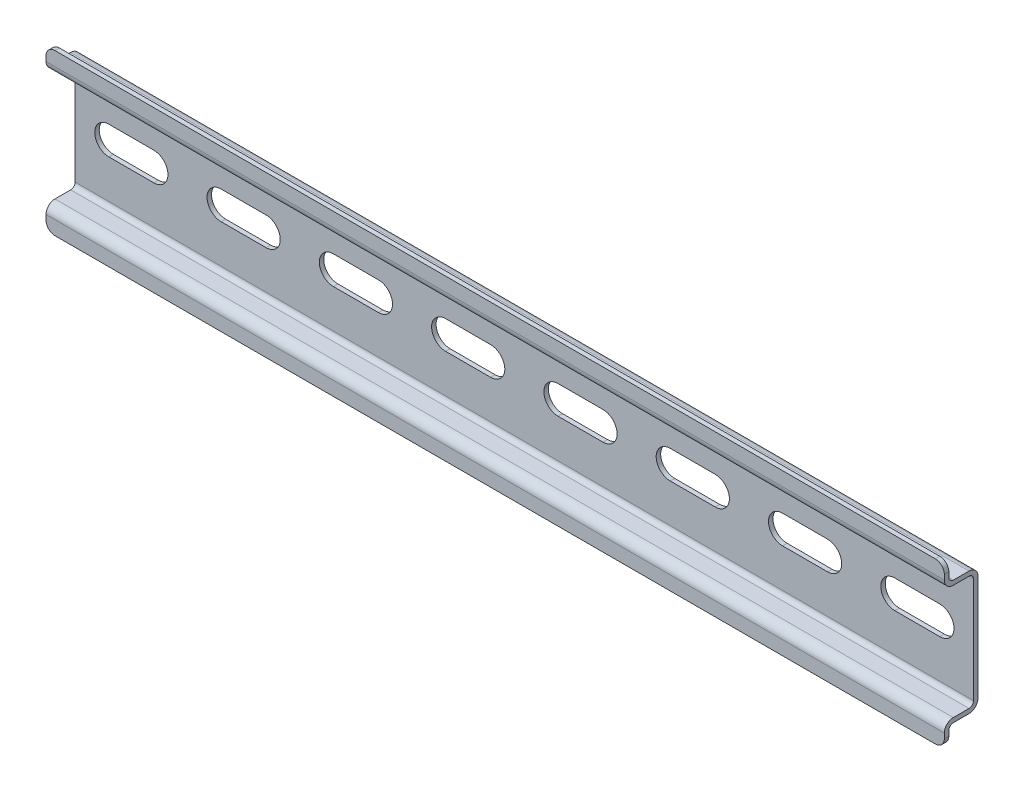
SolidWorks part; units mm, degrees
material "AISI 1045 Steel, cold drawn"
ref_plane "Front" through (0, 0, 0) normal (0, 0, 1) x (1, 0, 0)
ref_plane "Top" through (0, 0, 0) normal (0, 1, 0) x (1, 0, 0)
ref_plane "Right" through (0, 0, 0) normal (1, 0, 0) x (0, 0, -1)
sketch "Sketch1" plane through (0, 0, 0) normal (1, 0, 0) x (0, 0, -1)
  line L0 (0, 0) -> (0, 3.1)
  line L1 (2, 5.1) -> (5.5, 5.1)
  line L2 (6.5, 6.1) -> (6.5, 29.6)
  line L3 (5.5, 30.6) -> (2, 30.6)
  line L4 (0, 32.6) -> (0, 35.7)
  line L5 (6.5, 17.85) -> (-5.5369, 17.85) construction
  line L6 (1, 0) -> (1, 3.1)
  line L7 (2, 4.1) -> (5.5, 4.1)
  line L8 (7.5, 6.1) -> (7.5, 29.6)
  line L9 (5.5, 31.6) -> (2, 31.6)
  line L10 (1, 32.6) -> (1, 35.7)
  line L11 (0, 0) -> (1, 0)
  line L12 (0, 35.7) -> (1, 35.7)
  arc A0 (2, 30.6) -> (0, 32.6) centre (2, 32.6) cw
  arc A1 (0, 3.1) -> (2, 5.1) centre (2, 3.1) cw
  arc A2 (6.5, 29.6) -> (5.5, 30.6) centre (5.5, 29.6) ccw
  arc A3 (5.5, 5.1) -> (6.5, 6.1) centre (5.5, 6.1) ccw
  arc A4 (1, 3.1) -> (2, 4.1) centre (2, 3.1) cw
  arc A5 (5.5, 4.1) -> (7.5, 6.1) centre (5.5, 6.1) ccw
  arc A6 (7.5, 29.6) -> (5.5, 31.6) centre (5.5, 29.6) ccw
  arc A7 (2, 31.6) -> (1, 32.6) centre (2, 32.6) cw
  dimension "D1" = 2
  dimension "D2" = 1
  dimension "D3" = 6.5
  dimension "D4" = 35.7
  dimension "D5" = 25.5
  dimension "D6" = 1
extrude "Boss-Extrude1" add sketch "Sketch1" along normal blind 200
sketch "Sketch2" plane through (0, 0, 0) normal (0, 0, 1) x (1, 0, 0)
  line L0 (0, 17.85) -> (200, 17.85) construction
  line L1 (0, 29.6) -> (0, 6.1) construction
  line L2 (200, 29.6) -> (200, 6.1) construction
  line L3 (7.5, 17.85) -> (17.5, 17.85) construction
  line L4 (7.5, 21) -> (17.5, 21)
  line L5 (7.5, 14.7) -> (17.5, 14.7)
  arc A0 (7.5, 21) -> (7.5, 14.7) centre (7.5, 17.85) ccw
  arc A1 (17.5, 14.7) -> (17.5, 21) centre (17.5, 17.85) ccw
  point P8 (12.5, 17.85)
  dimension "D1" = 6.3
  dimension "D2" = 10
  dimension "D3" = 12.5
extrude "Cut-Extrude1" cut sketch "Sketch2" against normal through all
pattern_linear "LPattern1" count 10 spacing 25 along (1, 0, 0) of "Cut-Extrude1"
fillet "Fillet1" radius 2 4 edges at (200, 0, -0.5) (200, 35.7, -0.5) (0, 0, -0.5) (0, 35.7, -0.5)
equation "\"Length\"=200"
equation "\"D1@Boss-Extrude1\"=\"Length\""
equation "\"Hole Spacing\"=25"
equation "\"D3@LPattern1\"=\"Hole Spacing\""
